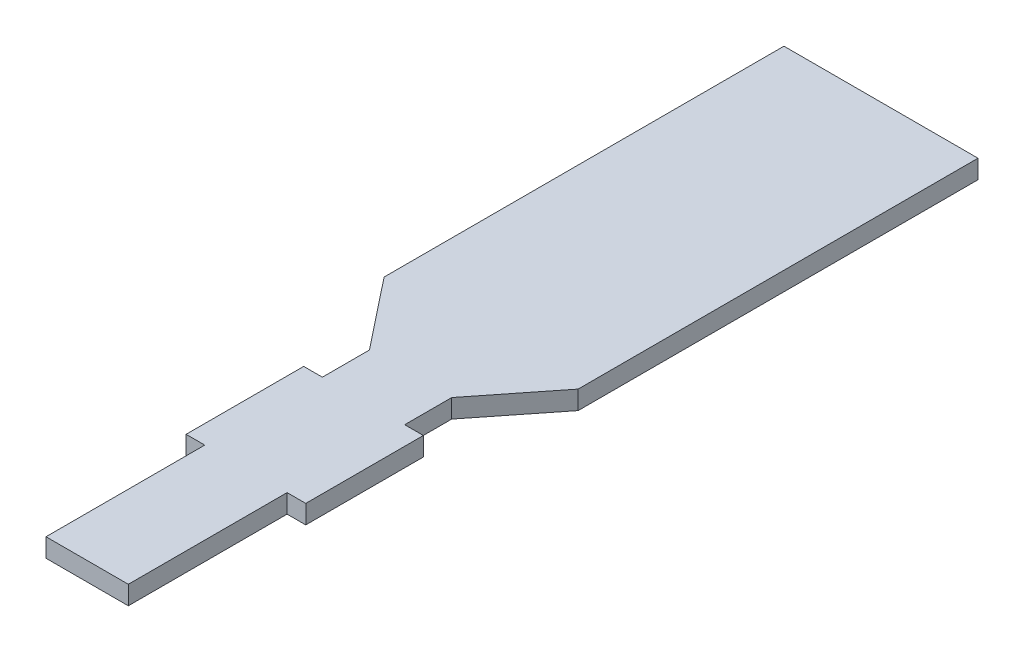
SolidWorks part; units mm, degrees
ref_plane "Front Plane" through (0, 0, 0) normal (0, 0, 1) x (1, 0, 0)
ref_plane "Top Plane" through (0, 0, 0) normal (0, 1, 0) x (1, 0, 0)
ref_plane "Right Plane" through (0, 0, 0) normal (1, 0, 0) x (0, 0, -1)
sketch "Sketch1" plane through (0, 0, 0) normal (0, 1, 0) x (1, 0, 0)
  line L0 (-16.5, 0) -> (16.5, 0)
  line L1 (16.5, 0) -> (16.5, -68)
  line L2 (16.5, -68) -> (7, -80)
  line L3 (7, -80) -> (7, -88)
  line L4 (7, -88) -> (10.175, -88)
  line L5 (10.175, -88) -> (10.175, -108)
  line L6 (10.175, -108) -> (7, -108)
  line L7 (7, -108) -> (7, -135)
  line L8 (7, -135) -> (-7, -135)
  line L9 (0, 0) -> (0, -135) construction
  line L10 (-7, -108) -> (-7, -135)
  line L11 (-10.175, -108) -> (-7, -108)
  line L12 (-10.175, -88) -> (-10.175, -108)
  line L13 (-7, -88) -> (-10.175, -88)
  line L14 (-7, -80) -> (-7, -88)
  line L15 (-16.5, -68) -> (-7, -80)
  line L16 (-16.5, 0) -> (-16.5, -68)
  dimension "D1" = 68
  dimension "D2" = 3.175
  dimension "D3" = 20
  dimension "D4" = 20
  dimension "D5" = 27
  dimension "D6" = 16.5
  dimension "D7" = 7
  dimension "D8" = 12
extrude "Boss-Extrude1" add sketch "Sketch1" along normal blind 3.175
